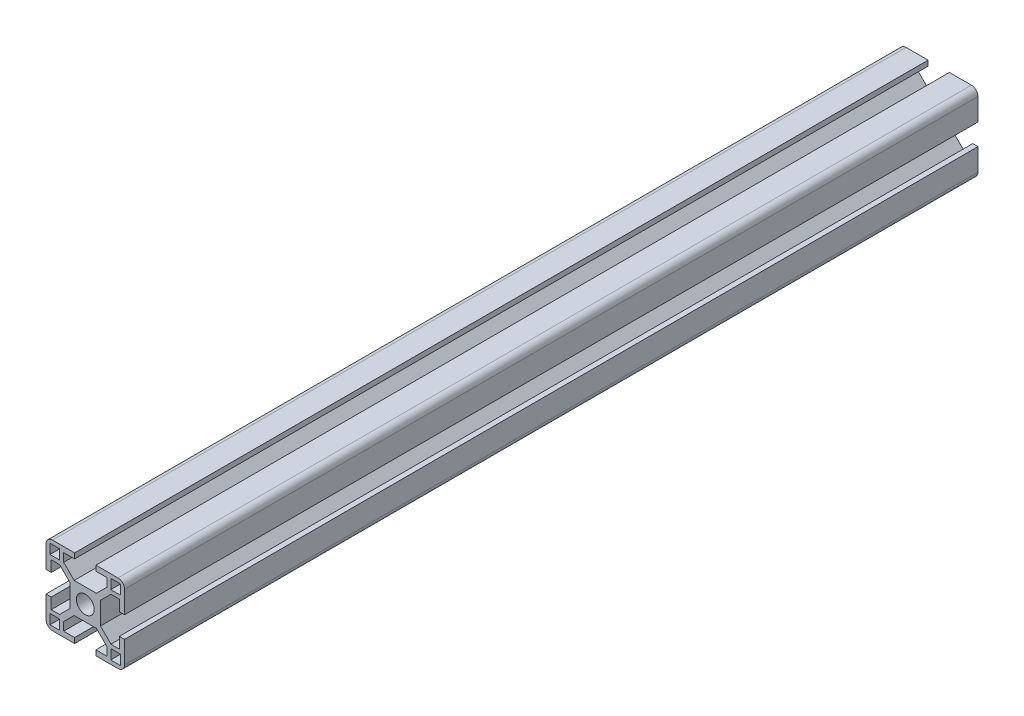
SolidWorks part; units mm, degrees
material "1060 Alloy"
ref_plane "Front" through (0, 0, 0) normal (0, 0, 1) x (1, 0, 0)
ref_plane "Top" through (0, 0, 0) normal (0, 1, 0) x (1, 0, 0)
ref_plane "Right" through (0, 0, 0) normal (1, 0, 0) x (0, 0, -1)
sketch3d "3DSketch1"
  line L0 (0, 0, 162.9999) -> (0, 0, -162.9999)
  dimension "D1" = 325.9998
other "3030 3030 PROFILE ZYLTECH(1)"
ref_plane "Plane1" through (0, 0, 162.9999) normal (0, 0, -1) x (1, 0, 0)
sketch "Sketch11" plane through (0, 0, 162.9999) normal (0, 0, -1) x (1, 0, 0)
  line L0 (-8.25, -13) -> (8.25, -13) construction
  line L1 (-13, -8.25) -> (-13, 8.25) construction
  line L2 (8.25, 13) -> (-8.25, 13) construction
  line L3 (13, 8.25) -> (13, -8.25) construction
  line L4 (-12.5, -15) -> (12.5, -15) construction
  line L5 (-15, -12.5) -> (-15, 12.5) construction
  line L6 (12.5, 15) -> (-12.5, 15) construction
  line L7 (15, 12.5) -> (15, -12.5) construction
  line L8 (-15, 0) -> (-13, 0) construction
  line L9 (-13, 0) -> (13, 0) construction
  line L10 (13, 0) -> (15, 0) construction
  line L11 (0, 15) -> (0, 13) construction
  line L12 (0, 13) -> (0, -13) construction
  line L13 (0, -13) -> (0, -15) construction
  line L14 (0, 0) -> (-15, 15) construction
  line L15 (-15, -15) -> (0, 0) construction
  line L16 (0, 0) -> (15, -15) construction
  line L17 (15, 15) -> (0, 0) construction
  line L18 (-9.8056, -8.25) -> (-5.8, -4.2444)
  line L19 (-9.8056, 8.25) -> (-5.8, 4.2444)
  line L20 (-8.25, 9.8056) -> (-4.2444, 5.8)
  line L21 (-8.25, -9.8056) -> (-4.2444, -5.8)
  line L22 (8.25, -9.8056) -> (4.2444, -5.8)
  line L23 (9.8056, -8.25) -> (5.8, -4.2444)
  line L24 (8.25, 9.8056) -> (4.2444, 5.8)
  line L25 (9.8056, 8.25) -> (5.8, 4.2444)
  line L26 (-5.8, 4.2444) -> (-4.2444, 5.8) construction
  line L27 (4.2444, 5.8) -> (5.8, 4.2444) construction
  line L28 (4.2444, -5.8) -> (5.8, -4.2444) construction
  line L29 (-5.8, -4.2444) -> (-4.2444, -5.8) construction
  line L30 (-5.8, -4.2444) -> (-5.8, 4.2444)
  line L31 (-4.2444, 5.8) -> (4.2444, 5.8)
  line L32 (5.8, 4.2444) -> (5.8, -4.2444)
  line L33 (4.2444, -5.8) -> (-4.2444, -5.8)
  line L34 (-8.25, 13) -> (-4.07, 13)
  line L35 (-4.07, 13) -> (-4.07, 15)
  line L36 (-4.07, 15) -> (-12.5, 15)
  line L37 (-15, 12.5) -> (-15, 4.07)
  line L38 (-15, 4.07) -> (-13, 4.07)
  line L39 (-13, 4.07) -> (-13, 8.25)
  line L40 (-15, -12.5) -> (-15, -4.07)
  line L41 (-15, -4.07) -> (-13, -4.07)
  line L42 (-13, -4.07) -> (-13, -8.25)
  line L43 (-12.5, -15) -> (-4.07, -15)
  line L44 (-4.07, -15) -> (-4.07, -13)
  line L45 (-4.07, -13) -> (-8.25, -13)
  line L46 (12.5, -15) -> (4.07, -15)
  line L47 (4.07, -15) -> (4.07, -13)
  line L48 (4.07, -13) -> (8.25, -13)
  line L49 (15, -12.5) -> (15, -4.07)
  line L50 (15, -4.07) -> (13, -4.07)
  line L51 (13, -4.07) -> (13, -8.25)
  line L52 (13, 8.25) -> (13, 4.07)
  line L53 (13, 4.07) -> (15, 4.07)
  line L54 (15, 4.07) -> (15, 12.5)
  line L55 (12.5, 15) -> (4.07, 15)
  line L56 (4.07, 15) -> (4.07, 13)
  line L57 (4.07, 13) -> (8.25, 13)
  line L58 (-4.07, 14) -> (4.07, 14) construction
  line L59 (-14, 4.07) -> (-14, -4.07) construction
  line L60 (14, 4.07) -> (14, -4.07) construction
  line L61 (-4.07, -14) -> (4.07, -14) construction
  line L62 (-13, 8.25) -> (-9.8056, 8.25)
  line L63 (-8.25, 13) -> (-8.25, 9.8056)
  line L64 (9.75, 11.625) -> (8.25, 11.625) construction
  line L65 (8.25, 13) -> (8.25, 9.8056)
  line L66 (13, 8.25) -> (9.8056, 8.25)
  line L67 (13, -8.25) -> (9.8056, -8.25)
  line L68 (8.25, -9.8056) -> (8.25, -13)
  line L69 (-8.25, -13) -> (-8.25, -9.8056)
  line L70 (-9.8056, -8.25) -> (-13, -8.25)
  line L71 (-13.5, -11.625) -> (-15, -11.625) construction
  line L72 (-9.75, 9.75) -> (-13.5, 9.75)
  line L73 (-9.75, 9.75) -> (-9.75, 13.5)
  line L74 (-9.75, 13.5) -> (-13.5, 13.5)
  line L75 (9.75, 9.75) -> (13.5, 9.75)
  line L76 (9.75, 9.75) -> (9.75, 13.5)
  line L77 (9.75, 13.5) -> (13.5, 13.5)
  line L78 (13.5, 9.75) -> (13.5, 13.5)
  line L79 (-9.75, -11.625) -> (-8.25, -11.625) construction
  line L87 (13.5, 11.625) -> (15, 11.625) construction
  line L88 (-13.5, 9.75) -> (-13.5, 13.5)
  line L89 (-9.75, -9.75) -> (-13.5, -9.75)
  line L90 (-9.75, -9.75) -> (-9.75, -13.5)
  line L91 (-9.75, -13.5) -> (-13.5, -13.5)
  line L92 (-13.5, -9.75) -> (-13.5, -13.5)
  line L93 (9.75, -9.75) -> (13.5, -9.75)
  line L94 (9.75, -9.75) -> (9.75, -13.5)
  line L95 (9.75, -13.5) -> (13.5, -13.5)
  line L96 (13.5, -9.75) -> (13.5, -13.5)
  arc A0 (15, 12.5) -> (12.5, 15) centre (12.5, 12.5) ccw
  arc A1 (12.5, -15) -> (15, -12.5) centre (12.5, -12.5) ccw
  arc A2 (-15, -12.5) -> (-12.5, -15) centre (-12.5, -12.5) ccw
  arc A3 (-12.5, 15) -> (-15, 12.5) centre (-12.5, 12.5) ccw
  circle A8 centre (0, 0) radius 3.4
  point P6 (-15, -15)
  point P23 (5.0222, 5.0222)
  point P33 (-15, 15)
  point P35 (15, 15)
  point P36 (15, -15)
  point P44 (-15, 0)
  point P47 (-5.0222, 5.0222)
  point P48 (-5.0222, -5.0222)
  point P49 (5.0222, -5.0222)
  point P71 (0, 14)
  point P78 (0, -14)
  point P79 (14, 0)
  point P80 (0, 15)
  point P81 (-14, 0)
  point P82 (15, 0)
  point P83 (0, -15)
  point P103 (0, 0)
  point P104 (0, 0)
  point P105 (0, 0)
  dimension "D1" = 2.5
  dimension "D2" = 6.8
  dimension "D3" = 2.2
  dimension "D4" = 16.5
  dimension "D5" = 3.75
  dimension "D7" = 11.6
  dimension "D8" = 8.14
  dimension "Thickness" = 2
  dimension "V_leg" = 30
  dimension "H_leg" = 30
hole_wizard "CBORE for M6 Hex Head Bolt1" positions "Sketch13" profile "Sketch14" counterbore size "M6" standard "ANSI Metric"
sketch "Sketch13" plane through (-15, 0, 0) normal (-1, 0, 0) x (0, 0, 1)
  line L0 (-165.0105, 0) -> (165.0105, 0)
  point P0 (-165.0105, 0)
  point P2 (165.0105, 0)
  dimension "D1" = 330.0209
sketch "Sketch14" plane through (-15, 0, -165.0105) normal (0, 1, 0) x (0, 0, 1)
  line L0 (0, 0) -> (0, 30)
  line L1 (0, 30) -> (3.3, 30)
  line L3 (3.3, 30) -> (3.3, 4.38)
  line L4 (3.3, 4.38) -> (7.275, 4.38)
  line L5 (7.275, 4.38) -> (7.275, 0)
  line L7 (7.275, 0) -> (0, 0)
  line L11 (0, -6.35) -> (0, 107.95) construction
  dimension "Thru Hole Dia." = 6.6
  dimension "Thru Hole Depth" = 30
  dimension "C'Bore Dia." = 14.55
  dimension "C'Bore Depth" = 4.38
hole_wizard "CBORE for M6 Hex Head Bolt2" positions "Sketch15" profile "Sketch16" counterbore size "M6" standard "ANSI Metric"
sketch "Sketch15" plane through (0, -15, 0) normal (0, -1, 0) x (-1, 0, 0)
  point P0 (0, 59.7526)
  dimension "D1" = 59.7526
sketch "Sketch16" plane through (0, -15, -59.7526) normal (1, 0, 0) x (0, 0, -1)
  line L0 (0, 0) -> (0, 30)
  line L1 (0, 30) -> (3.3, 30)
  line L3 (3.3, 30) -> (3.3, 4.38)
  line L4 (3.3, 4.38) -> (7.275, 4.38)
  line L5 (7.275, 4.38) -> (7.275, 0)
  line L7 (7.275, 0) -> (0, 0)
  line L11 (0, -6.35) -> (0, 107.95) construction
  dimension "Thru Hole Dia." = 6.6
  dimension "Thru Hole Depth" = 30
  dimension "C'Bore Dia." = 14.55
  dimension "C'Bore Depth" = 4.38
